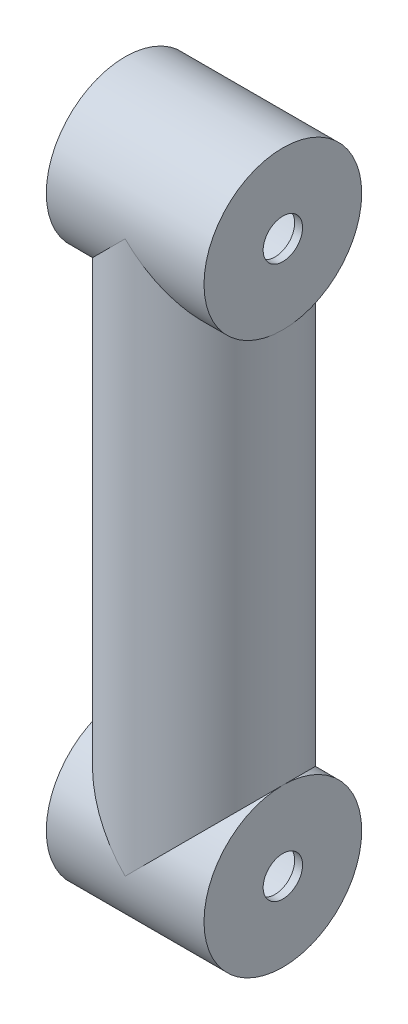
SolidWorks part; units mm, degrees
ref_plane "Front Plane" through (0, 0, 0) normal (0, 0, 1) x (1, 0, 0)
ref_plane "Top Plane" through (0, 0, 0) normal (0, 1, 0) x (1, 0, 0)
ref_plane "Right Plane" through (0, 0, 0) normal (1, 0, 0) x (0, 0, -1)
sketch "Sketch1" plane through (0, 0, 0) normal (0, 1, 0) x (1, 0, 0)
  circle A0 centre (0, 0) radius 20
  circle A1 centre (0, 0) radius 18
  dimension "D1" = 40
  dimension "D2" = 2
extrude "Boss-Extrude1" add sketch "Sketch1" along normal blind 70
sketch "Sketch2" plane through (0, 0, 0) normal (1, 0, 0) x (0, 0, -1)
  line L0 (18, 70) -> (-18, 70) construction
  circle A0 centre (0, 70) radius 20
extrude "Cut-Extrude1" cut sketch "Sketch2" against normal mid plane 40
sketch "Sketch3" plane through (0, 0, 0) normal (1, 0, 0) x (0, 0, -1)
  circle A0 centre (0, 70) radius 20
  circle A1 centre (0, 70) radius 18
  dimension "D1" = 2
extrude "Boss-Extrude2" add sketch "Sketch3" along normal mid plane 40
sketch "Sketch4" plane through (20, 0, 0) normal (1, 0, 0) x (0, 0, -1)
  circle A0 centre (0, 70) radius 18
  circle A1 centre (0, 70) radius 5
extrude "Boss-Extrude3" add sketch "Sketch4" against normal blind 2 contours A1 | A0
sketch "Sketch5" plane through (0, 0, 0) normal (0, -1, 0) x (1, 0, 0)
  circle A0 centre (0, 0) radius 5
extrude "Cut-Extrude2" cut sketch "Sketch5" against normal blind 70
mirror "Mirror1" about plane through (0, 0, 0) normal (0, 1, 0) of "Cut-Extrude2", "Boss-Extrude3", "Boss-Extrude1", "Cut-Extrude1", "Boss-Extrude2"
